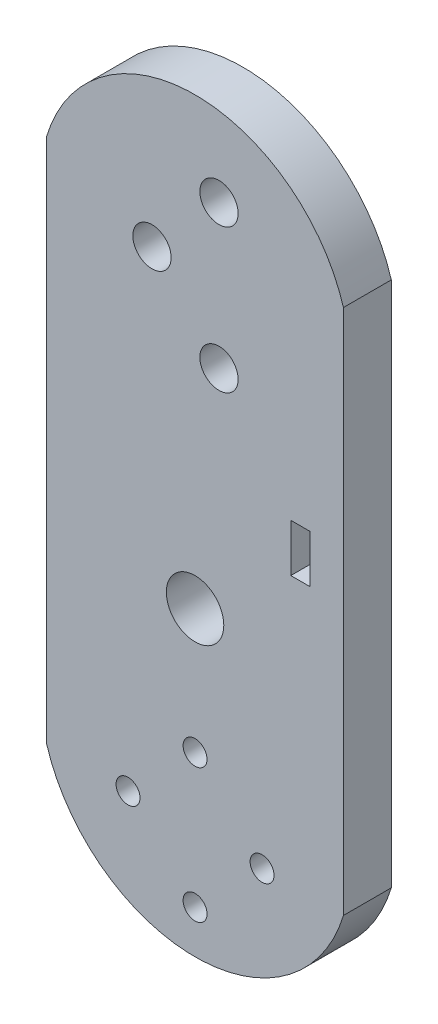
SolidWorks part; units mm, degrees
ref_plane "Front Plane" through (0, 0, 0) normal (0, 0, 1) x (1, 0, 0)
ref_plane "Top Plane" through (0, 0, 0) normal (0, 1, 0) x (1, 0, 0)
ref_plane "Right Plane" through (0, 0, 0) normal (1, 0, 0) x (0, 0, -1)
sketch "Sketch1" plane through (0, 0, 0) normal (0, 0, 1) x (1, 0, 0)
  line L0 (-3.8641, 0) -> (3.4161, 0) construction
  line L1 (0, 3.4595) -> (0, -3.5064) construction
  line L2 (-15.5247, -11.5) -> (18.1431, -11.5) construction
  line L3 (-12.2626, 27.5) -> (11.4962, 27.5) construction
  line L4 (-15.5, 55) -> (-15.5, 0)
  line L5 (15.5, 55) -> (15.5, 0)
  line L6 (-19.9755, 66.5) -> (24.8945, 66.5) construction
  line L8 (10, 33) -> (12, 33)
  line L9 (10, 33) -> (10, 28)
  line L10 (10, 28) -> (12, 28)
  line L11 (12, 33) -> (12, 28)
  circle A0 centre (0, 0) radius 7 construction
  circle A1 centre (0, 7) radius 1.25
  circle A2 centre (7, 0) radius 1.25
  circle A3 centre (0, -7) radius 1.25
  circle A4 centre (-7, 0) radius 1.25
  arc A5 (-15.5, 0) -> (15.5, 0) centre (0, 4.6957) ccw
  arc A7 (-15.5, 55) -> (15.5, 55) centre (0, 50.3043) cw
  circle A8 centre (0, 20) radius 3
  circle A9 centre (2.5, 58) radius 2
  circle A10 centre (2.5, 43) radius 2
  circle A11 centre (-4.5, 50.5) radius 2
  point P3 (0, 7)
  point P4 (7, 0)
  point P5 (0, -7)
  point P6 (-7, 0)
  dimension "D1" = 14
  dimension "D2" = 2.5
  dimension "D6" = 6
  dimension "D9" = 4
  dimension "D3" = 11.5
  dimension "D4" = 15.5
  dimension "D5" = 15.5
  dimension "D7" = 20
  dimension "D8" = 27.5
  dimension "D10" = 15
  dimension "D11" = 7.5
  dimension "D12" = 7
  dimension "D13" = 8.5
  dimension "D14" = 13
  dimension "D15" = 2
  dimension "D16" = 5
  dimension "D17" = 3.5
  dimension "D18" = 10
extrude "Boss-Extrude1" add sketch "Sketch1" along normal blind 5
